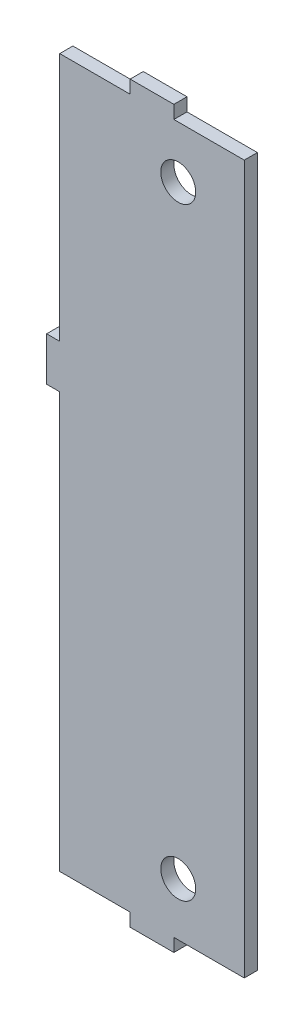
SolidWorks part; units mm, degrees
ref_plane "Front Plane" through (0, 0, 0) normal (0, 0, 1) x (1, 0, 0)
ref_plane "Top Plane" through (0, 0, 0) normal (0, 1, 0) x (1, 0, 0)
ref_plane "Right Plane" through (0, 0, 0) normal (1, 0, 0) x (0, 0, -1)
sketch "Sketch1" plane through (0, 0, 0) normal (0, 0, 1) x (1, 0, 0)
  line L16 (-5, 0) -> (5, 0)
  line L25 (-21.1, -3) -> (-21.1, -60)
  line L27 (-5, 0) -> (-5, -3)
  line L28 (5, 0) -> (5, -3)
  line L30 (-21.1, -60) -> (-24.1, -60)
  line L35 (5, -3) -> (21.1, -3)
  line L36 (-5, -3) -> (-21.1, -3)
  line L37 (-24.1, -60) -> (-24.1, -70)
  line L39 (-24.1, -70) -> (-21.1, -70)
  line L40 (-21.1, -70) -> (-21.1, -165)
  line L41 (-21.1, -165) -> (-5, -165)
  line L43 (-5, -165) -> (-5, -168)
  line L44 (-5, -168) -> (5, -168)
  line L45 (5, -168) -> (5, -165)
  line L46 (5, -165) -> (21.1, -165)
  line L47 (21.1, -3) -> (21.1, -165)
  point P3 (0, 0)
  dimension "D1" = 10
  dimension "D2" = 3
  dimension "D3" = 16.1
  dimension "D4" = 16.1
  dimension "D5" = 3
  dimension "D6" = 57
  dimension "D7" = 3
  dimension "D8" = 95
  dimension "D9" = 3
  dimension "D10" = 10
  dimension "D11" = 16.1
  dimension "D12" = 3
  dimension "D13" = 10
  dimension "D14" = 3
  dimension "D15" = 16.1
extrude "Boss-Extrude1" add sketch "Sketch1" along normal mid plane 3
sketch "Sketch2" plane through (0, 0, 1.5) normal (0, 0, 1) x (1, 0, 0)
  line L0 (21.1, -3) -> (6, -3) construction
  line L2 (6, -14.9) -> (6, -3) construction
  line L3 (-24.1, -60) -> (-24.1, -70) construction
  line L4 (-21.1, -60) -> (-24.1, -60) construction
  line L5 (6, -14.9) -> (6, -152.9) construction
  point P10 (6, -14.9)
  point P12 (6, -152.9)
  dimension "D1" = 15.1
  dimension "D2" = 11.9
  dimension "D3" = 3
  dimension "D4" = 30.1
  dimension "D5" = 138
hole_wizard "Ø8.0 (8) Diameter Hole1" positions "Sketch5" profile "Sketch6" hole size "Ø8.0" standard "AS" end condition through all
sketch "Sketch5" plane through (0, 0, 1.5) normal (0, 0, 1) x (1, 0, 0)
  point P0 (6, -14.9)
  point P3 (6, -152.9)
sketch "Sketch6" plane through (6, -14.9, 1.5) normal (1, 0, 0) x (0, -1, 0)
  line L0 (0, 0) -> (0, 3)
  line L1 (0, 3) -> (4, 3)
  line L2 (4, 3) -> (4, 0)
  line L5 (4, 0) -> (0, 0)
  line L11 (0, -6.35) -> (0, 107.95) construction
  dimension "Thru Hole Dia." = 8
  dimension "Thru Hole Depth" = 3
